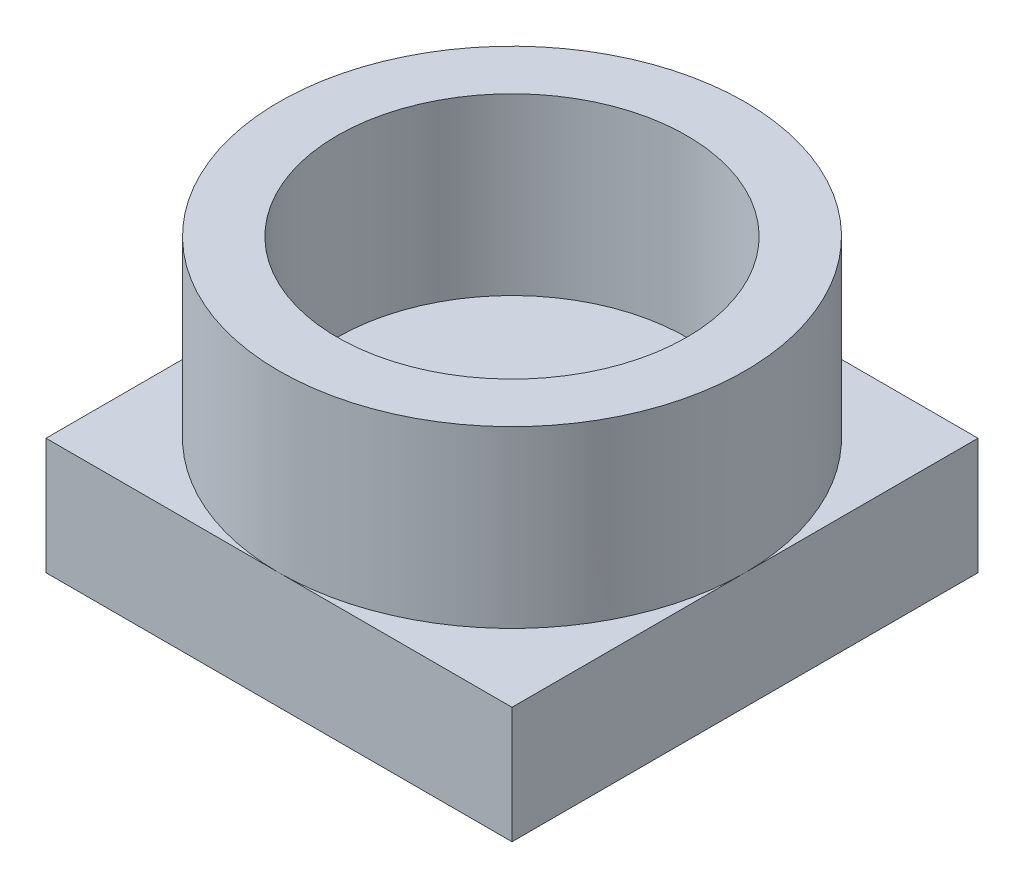
SolidWorks part; units mm, degrees
ref_plane "Ön Düzlem" through (0, 0, 0) normal (0, 0, 1) x (1, 0, 0)
ref_plane "Üst Düzlem" through (0, 0, 0) normal (0, 1, 0) x (1, 0, 0)
ref_plane "Sağ Düzlem" through (0, 0, 0) normal (1, 0, 0) x (0, 0, -1)
sketch "Çizim1" plane through (0, 0, 0) normal (0, 1, 0) x (1, 0, 0)
  line L1 (-4, -4) -> (4, -4)
  line L2 (-4, -4) -> (-4, 4)
  line L3 (-4, 4) -> (4, 4)
  line L4 (4, -4) -> (4, 4)
  line L5 (-4, -4) -> (4, 4) construction
  line L6 (-4, 4) -> (4, -4) construction
  point P0 (0, 0)
  dimension "D1" = 8
  dimension "D2" = 8
extrude "Yükseklik-Ekstrüzyon1" add sketch "Çizim1" along normal blind 2
sketch "Çizim2" plane through (0, 2, 0) normal (0, 1, 0) x (1, 0, 0)
  circle A0 centre (0, 0) radius 4
extrude "Ekstrüzyon-İnce1" add sketch "Çizim2" along normal blind 3 thin thin type one direction reverse wall 1
